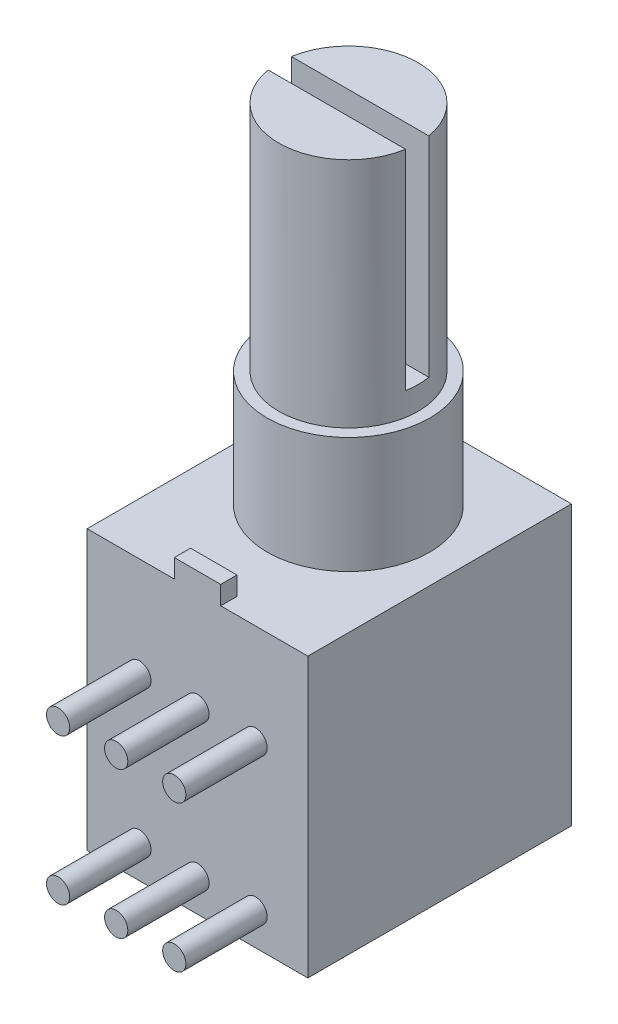
SolidWorks part; units mm, degrees
ref_plane "Front Plane" through (0, 0, 0) normal (0, 0, 1) x (1, 0, 0)
ref_plane "Top Plane" through (0, 0, 0) normal (0, 1, 0) x (1, 0, 0)
ref_plane "Right Plane" through (0, 0, 0) normal (1, 0, 0) x (0, 0, -1)
sketch "Sketch2" plane through (0, 0, 0) normal (0, 1, 0) x (1, 0, 0)
  line L1 (-4.75, 4.85) -> (4.75, 4.85)
  line L2 (-4.75, 4.85) -> (-4.75, -6.5)
  line L3 (-4.75, -6.5) -> (4.75, -6.5)
  line L4 (4.75, 4.85) -> (4.75, -6.5)
  point P5 (0, 4.85)
  dimension "D1" = 4.85
  dimension "D2" = 6.5
  dimension "D3" = 9.5
extrude "Boss-Extrude1" add sketch "Sketch2" against normal blind 12
sketch "Sketch3" plane through (0, 0, 0) normal (0, 1, 0) x (1, 0, 0)
  circle A0 centre (0, 0) radius 3.5
  dimension "D1" = 7
extrude "Boss-Extrude2" add sketch "Sketch3" along normal blind 5
sketch "Sketch4" plane through (0, 5, 0) normal (0, 1, 0) x (1, 0, 0)
  circle A0 centre (0, 0) radius 3
  dimension "D1" = 6
extrude "Boss-Extrude3" add sketch "Sketch4" along normal blind 10
sketch "Sketch5" plane through (0, 15, 0) normal (0, 1, 0) x (1, 0, 0)
  line L1 (-5, -0.5) -> (5, -0.5)
  line L2 (-5, -0.5) -> (-5, 0.5)
  line L3 (-5, 0.5) -> (5, 0.5)
  line L4 (5, -0.5) -> (5, 0.5)
  line L5 (-5, -0.5) -> (5, 0.5) construction
  line L6 (-5, 0.5) -> (5, -0.5) construction
  point P0 (0, 0)
  dimension "D1" = 10
  dimension "D2" = 1
extrude "Cut-Extrude1" cut sketch "Sketch5" against normal blind 9
sketch "Sketch6" plane through (0, 0, 0) normal (0, 1, 0) x (1, 0, 0)
  line L0 (-4.75, -6.5) -> (4.75, -6.5) construction
  line L1 (-1, -6.5) -> (1, -6.5)
  line L2 (-1, -6.5) -> (-1, -5.8)
  line L3 (-1, -5.8) -> (1, -5.8)
  line L4 (1, -6.5) -> (1, -5.8)
  point P6 (0, -5.8)
  dimension "D1" = 2
  dimension "D2" = 0.7
extrude "Boss-Extrude4" add sketch "Sketch6" along normal blind 0.8
sketch "Sketch7" plane through (0, 0, 6.5) normal (0, 0, 1) x (1, 0, 0)
  line L0 (-4.75, 0) -> (-1, 0) construction
  circle A0 centre (-2.5, -4.3) radius 0.5
  circle A1 centre (0, -4.3) radius 0.5
  circle A2 centre (2.5, -4.3) radius 0.5
  circle A3 centre (0, -10.6) radius 0.5
  circle A4 centre (2.5, -10.6) radius 0.5
  circle A5 centre (-2.5, -10.6) radius 0.5
  dimension "D1" = 4.3
  dimension "D2" = 1
  dimension "D3" = 3
  dimension "D5" = 6.3
  dimension "D6" = 5
  dimension "D4" = 2
extrude "Boss-Extrude5" add sketch "Sketch7" along normal blind 3.5
